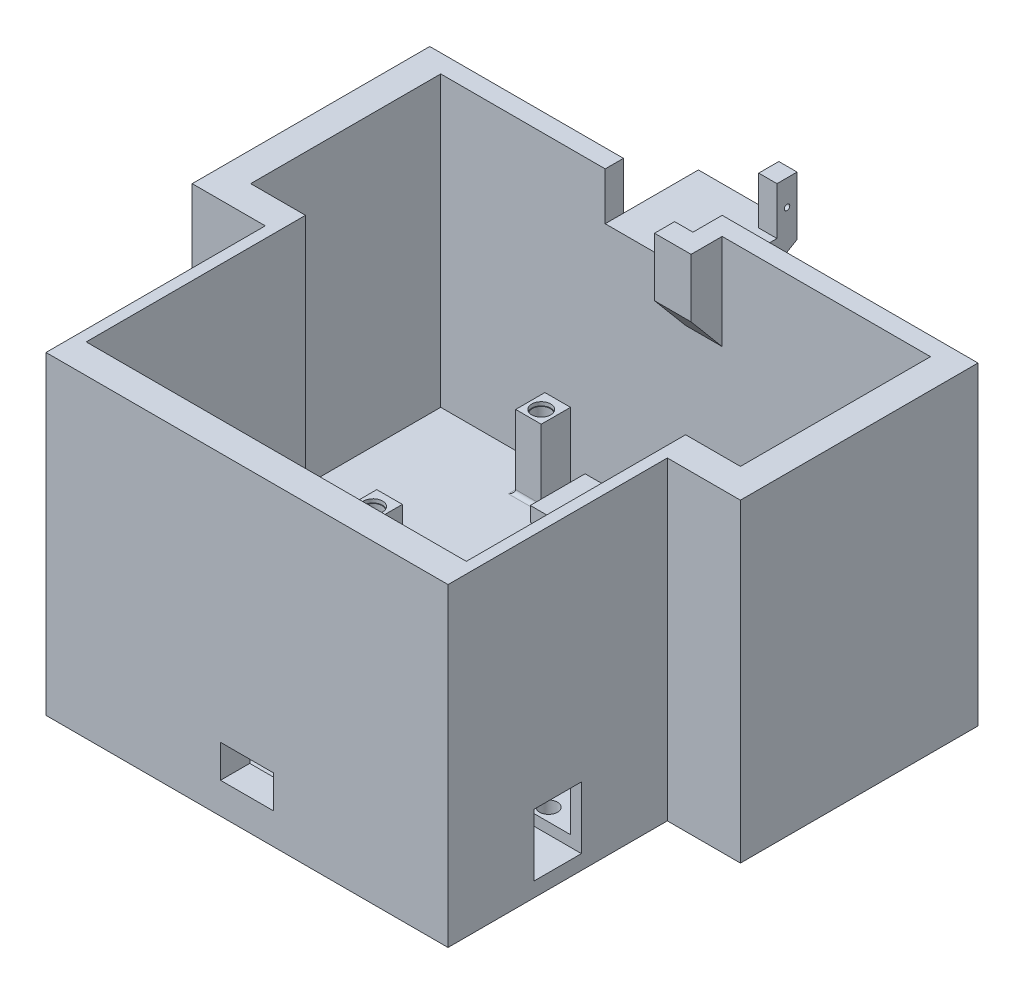
SolidWorks part; units mm, degrees
other "Marca2"
sketch "Croquis35" plane through (-75, 126, -70.5) normal (0, 1, 0) x (1, 0, 0)
other "Marca3"
sketch "Croquis45" plane through (-75, 0, 75) normal (-0.908, -0.0343, 0.4175) x (0.4055, -0.3225, 0.8553)
ref_plane "Alzado" through (0, 0, 0) normal (0, 0, 1) x (1, 0, 0)
ref_plane "Planta" through (0, 0, 0) normal (0, 1, 0) x (1, 0, 0)
ref_plane "Vista lateral" through (0, 0, 0) normal (1, 0, 0) x (0, 0, -1)
sketch "Croquis1" plane through (0, 0, 0) normal (0, 1, 0) x (1, 0, 0)
  line L1 (-75, -75) -> (75, -75)
  line L2 (-75, -75) -> (-75, 75)
  line L3 (-75, 75) -> (75, 75)
  line L4 (75, -75) -> (75, 75)
  line L5 (-75, -75) -> (75, 75) construction
  line L6 (-75, 75) -> (75, -75) construction
  point P0 (0, 0)
  dimension "D1" = 150
  dimension "D2" = 150
extrude "Saliente-Extruir2" add sketch "Croquis1" along normal blind 6
sketch "Croquis3" plane through (0, 6, 0) normal (0, 1, 0) x (1, 0, 0)
  line L0 (-75, 75) -> (-75, -75) construction
  line L1 (-75, -15) -> (-55, -15)
  line L2 (-75, -15) -> (-75, -75)
  line L3 (-75, -75) -> (-55, -75)
  line L4 (-55, -15) -> (-55, -75)
  line L5 (-75, -75) -> (75, -75) construction
  line L6 (0, 0) -> (0, -11.1427) construction
  line L7 (75, -75) -> (55, -75)
  line L8 (55, -15) -> (55, -75)
  line L9 (75, -15) -> (55, -15)
  line L10 (75, -15) -> (75, -75)
  dimension "D1" = 60
  dimension "D2" = 20
extrude "Cortar-Extruir2" cut sketch "Croquis3" against normal through all
sketch "Croquis4" plane through (0, 6, 0) normal (0, 1, 0) x (1, 0, 0)
  line L0 (75, -15) -> (75, 75) construction
  line L1 (-75, 75) -> (75, 75)
  line L2 (-75, 75) -> (-75, 50)
  line L3 (-75, 50) -> (75, 50)
  line L4 (75, 75) -> (75, 50)
  line L6 (-55, -75) -> (55, -75) construction
  dimension "D1" = 125
extrude "Cortar-Extruir3" cut sketch "Croquis4" against normal through all
sketch "Croquis5" plane through (0, 6, 0) normal (0, 1, 0) x (1, 0, 0)
  line L18 (67, -7) -> (67, 42)
  line L19 (67, 42) -> (-67, 42)
  line L20 (-67, 42) -> (-67, -7)
  line L21 (-67, -7) -> (-47, -7)
  line L22 (-47, -7) -> (-47, -67)
  line L23 (-47, -67) -> (47, -67)
  line L24 (47, -67) -> (47, -7)
  line L25 (47, -7) -> (67, -7)
  line L26 (67, -7) -> (67, 42)
  line L27 (67, 42) -> (-67, 42)
  line L28 (-67, 42) -> (-67, -7)
  line L29 (-67, -7) -> (-47, -7)
  line L30 (-47, -7) -> (-47, -67)
  line L31 (-47, -67) -> (47, -67)
  line L32 (47, -67) -> (47, -7)
  line L33 (47, -7) -> (67, -7)
  line L42 (75, -15) -> (75, 50)
  line L43 (75, 50) -> (-75, 50)
  line L44 (-75, 50) -> (-75, -15)
  line L45 (-75, -15) -> (-55, -15)
  line L46 (-55, -15) -> (-55, -75)
  line L47 (-55, -75) -> (55, -75)
  line L48 (55, -75) -> (55, -15)
  line L49 (55, -15) -> (75, -15)
  line L50 (75, -15) -> (75, 50)
  line L51 (75, 50) -> (-75, 50)
  line L52 (-75, 50) -> (-75, -15)
  line L53 (-75, -15) -> (-55, -15)
  line L54 (-55, -15) -> (-55, -75)
  line L55 (-55, -75) -> (55, -75)
  line L56 (55, -75) -> (55, -15)
  line L57 (55, -15) -> (75, -15)
  dimension "D1" = 8
  dimension "D2" = 0
extrude "Saliente-Extruir3" add sketch "Croquis5" along normal blind 80
sketch "Croquis6" plane through (0, 86, 0) normal (0, 1, 0) x (1, 0, 0)
  line L0 (-55, -45) -> (55, -45) construction
  line L1 (-55, -15) -> (-55, -75) construction
  line L2 (55, -75) -> (55, -15) construction
  line L3 (-47, -7) -> (-47, -67) construction
  line L4 (-63, -51.5) -> (-47, -51.5)
  line L5 (-63, -51.5) -> (-63, -38.5)
  line L6 (-63, -38.5) -> (-47, -38.5)
  line L7 (-47, -51.5) -> (-47, -38.5)
  line L8 (-63, -51.5) -> (-47, -38.5) construction
  line L9 (-63, -38.5) -> (-47, -51.5) construction
  line L10 (0, 0) -> (0, -5.6083) construction
  line L11 (63, -38.5) -> (47, -38.5)
  line L12 (47, -51.5) -> (47, -38.5)
  line L13 (63, -51.5) -> (47, -51.5)
  line L14 (63, -51.5) -> (63, -38.5)
  dimension "D1" = 13
extrude "Cortar-Extruir5" cut sketch "Croquis6" against normal up to surface (80 mm away) up to face at (0, 6, 9.75)
sketch "Croquis8" plane through (0, 6, 0) normal (0, 1, 0) x (1, 0, 0)
  line L0 (-55, -45) -> (55, -45) construction
  line L1 (-55, -51.5) -> (-55, -38.5) construction
  line L2 (55, -38.5) -> (55, -51.5) construction
  line L3 (-47, -7) -> (-47, -38.5) construction
  line L4 (-47, -38.5) -> (-26.5, -38.5)
  line L5 (-47, -38.5) -> (-47, -51.5)
  line L6 (-47, -51.5) -> (-26.5, -51.5)
  line L7 (-26.5, -38.5) -> (-26.5, -51.5)
  line L8 (0, 0) -> (0, -18.3886) construction
  line L9 (47, -51.5) -> (26.5, -51.5)
  line L10 (26.5, -38.5) -> (26.5, -51.5)
  line L11 (47, -38.5) -> (26.5, -38.5)
  line L12 (47, -38.5) -> (47, -51.5)
  point P12 (-26.5, -45)
  dimension "D1" = 13
  dimension "D2" = 20.5
sketch "Croquis10" plane through (0, 0, 0) normal (0, -1, 0) x (1, 0, 0)
  line L0 (-75, -50) -> (75, -50) construction
  line L1 (-27.5, -50) -> (27.5, -50)
  line L2 (-27.5, -50) -> (-27.5, -25)
  line L3 (-27.5, -25) -> (27.5, -25)
  line L4 (27.5, -50) -> (27.5, -25)
  point P6 (0, -25)
  dimension "D1" = 55
  dimension "D2" = 25
extrude "Cortar-Extruir6" cut sketch "Croquis10" against normal blind 5
extrude "Cortar-Extruir7" cut sketch "Croquis8" against normal blind 2
sketch "Croquis12" plane through (0, 6, 0) normal (0, 1, 0) x (1, 0, 0)
  line L0 (-47, -38.5) -> (-47, -51.5) construction
  line L1 (-55, -38.5) -> (-47, -38.5)
  line L2 (-55, -38.5) -> (-55, -51.5)
  line L3 (-55, -51.5) -> (-47, -51.5)
  line L4 (-47, -38.5) -> (-47, -51.5)
  line L5 (-47, -51.5) -> (-47, -38.5) construction
  line L6 (0, 0) -> (0, -14.0834) construction
  line L7 (55, -51.5) -> (47, -51.5)
  line L8 (47, -38.5) -> (47, -51.5)
  line L9 (55, -38.5) -> (47, -38.5)
  line L10 (55, -38.5) -> (55, -51.5)
extrude "Cortar-Extruir8" cut sketch "Croquis12" against normal up to surface (2 mm away) up to face at (-36.75, 4, 45)
sketch "Croquis15" plane through (0, 6, 0) normal (0, 1, 0) x (1, 0, 0)
  line L16 (-47, -7) -> (-47, -38.5)
  line L17 (-47, -38.5) -> (-26.5, -38.5)
  line L18 (-26.5, -38.5) -> (-26.5, -51.5)
  line L19 (-26.5, -51.5) -> (-47, -51.5)
  line L20 (-47, -51.5) -> (-47, -67)
  line L21 (-47, -67) -> (47, -67)
  line L22 (47, -67) -> (47, -51.5)
  line L23 (47, -51.5) -> (26.5, -51.5)
  line L24 (26.5, -51.5) -> (26.5, -38.5)
  line L25 (26.5, -38.5) -> (47, -38.5)
  line L26 (47, -38.5) -> (47, -7)
  line L27 (47, -7) -> (67, -7)
  line L28 (67, -7) -> (67, 42)
  line L29 (67, 42) -> (-67, 42)
  line L30 (-67, 42) -> (-67, -7)
  line L31 (-67, -7) -> (-47, -7)
  line L32 (-47, -7) -> (-47, -38.5)
  line L33 (-47, -38.5) -> (-26.5, -38.5)
  line L34 (-26.5, -38.5) -> (-26.5, -51.5)
  line L35 (-26.5, -51.5) -> (-47, -51.5)
  line L36 (-47, -51.5) -> (-47, -67)
  line L37 (-47, -67) -> (47, -67)
  line L38 (47, -67) -> (47, -51.5)
  line L39 (47, -51.5) -> (26.5, -51.5)
  line L40 (26.5, -51.5) -> (26.5, -38.5)
  line L41 (26.5, -38.5) -> (47, -38.5)
  line L42 (47, -38.5) -> (47, -7)
  line L43 (47, -7) -> (67, -7)
  line L44 (67, -7) -> (67, 42)
  line L45 (67, 42) -> (-67, 42)
  line L46 (-67, 42) -> (-67, -7)
  line L47 (-67, -7) -> (-47, -7)
  dimension "D1" = 0
extrude "Saliente-Extruir6" add sketch "Croquis15" along normal blind 1
sketch "Croquis16" plane through (-55, 0, 0) normal (-1, 0, 0) x (0, 0, 1)
  line L0 (51.5, 16) -> (38.5, 16) construction
  line L1 (51.5, 86) -> (51.5, 4) construction
  line L2 (38.5, 4) -> (38.5, 86) construction
  line L3 (51.5, 4) -> (38.5, 4) construction
  dimension "D1" = 12
sketch "Croquis17" plane through (0, 86, 0) normal (0, 1, 0) x (1, 0, 0)
  line L0 (0, 0) -> (0, -9.7124) construction
  line L1 (-55, -38.5) -> (-47, -38.5)
  line L2 (-55, -38.5) -> (-55, -51.5)
  line L3 (-55, -51.5) -> (-47, -51.5)
  line L4 (-47, -38.5) -> (-47, -51.5)
  line L5 (55, -51.5) -> (47, -51.5)
  line L6 (47, -38.5) -> (47, -51.5)
  line L7 (55, -38.5) -> (47, -38.5)
  line L8 (55, -38.5) -> (55, -51.5)
extrude "Saliente-Extruir7" add sketch "Croquis17" against normal blind 65
sketch "Croquis20" plane through (0, 0, -50) normal (0, 0, -1) x (-1, 0, 0)
  line L0 (0, 0) -> (0, 36.986) construction
  line L2 (0, 73) -> (22, 73)
  line L3 (0, 73) -> (0, 86)
  line L4 (0, 86) -> (22, 86)
  line L5 (22, 73) -> (22, 86)
  line L6 (0, 73) -> (22, 86) construction
  line L7 (0, 86) -> (22, 73) construction
  line L8 (-75, 86) -> (75, 86) construction
  point P3 (11, 79.5)
  dimension "D1" = 13
  dimension "D2" = 22
extrude "Cortar-Extruir9" cut sketch "Croquis20" against normal up to next
sketch "Croquis23" plane through (0, 86, 0) normal (0, 1, 0) x (1, 0, 0)
  line L0 (-75, 50) -> (-75, -15) construction
  line L1 (-74, 11) -> (-68, 11)
  line L2 (-74, 11) -> (-74, 24)
  line L3 (-74, 24) -> (-68, 24)
  line L4 (-68, 11) -> (-68, 24)
  line L5 (-74, 11) -> (-68, 24) construction
  line L6 (-74, 24) -> (-68, 11) construction
  line L7 (-75, 50) -> (-75, -15) construction
  line L8 (0, 0) -> (0, 8.906) construction
  line L9 (74, 24) -> (68, 24)
  line L10 (68, 11) -> (68, 24)
  line L11 (74, 11) -> (68, 11)
  line L12 (74, 11) -> (74, 24)
  line L22 (-55, -75) -> (55, -75) construction
  line L23 (47, -67) -> (47, -75) construction
  line L24 (-6.5, -74) -> (6.5, -74)
  line L25 (-6.5, -74) -> (-6.5, -68)
  line L26 (-6.5, -68) -> (6.5, -68)
  line L27 (6.5, -74) -> (6.5, -68)
  line L28 (-6.5, -74) -> (6.5, -68) construction
  line L29 (-6.5, -68) -> (6.5, -74) construction
  line L30 (-47, -67) -> (47, -67) construction
  point P0 (-71, 17.5)
  point P12 (-75, 17.5)
  point P20 (0, -71)
  point P38 (0, -75)
  dimension "D1" = 4
  dimension "D2" = 6
  dimension "D3" = 13
  dimension "D4" = 13
  dimension "D5" = 6
  dimension "D6" = 1
extrude "Cortar-Extruir10" cut sketch "Croquis23" against normal blind 3
sketch "Croquis24" plane through (0, 73, 0) normal (0, 1, 0) x (1, 0, 0)
  line L0 (75, 50) -> (0, 50) construction
  line L1 (-22, 70.5) -> (0, 70.5)
  line L2 (-22, 70.5) -> (-22, 36.5)
  line L3 (-22, 36.5) -> (0, 36.5)
  line L4 (0, 70.5) -> (0, 36.5)
  dimension "D1" = 22
  dimension "D2" = 34
  dimension "D3" = 13.5
extrude "Saliente-Extruir9" add sketch "Croquis24" against normal blind 3
sketch "Croquis25" plane through (-22, 0, 0) normal (-1, 0, 0) x (0, 0, 1)
  line L0 (-70.5, 73) -> (-36.5, 73) construction
  line L1 (-42, 73) -> (-42, 102.2698) construction
  line L6 (-42, 70) -> (-36.5, 70) construction
  line L21 (-36.5, 73) -> (-36.5, 70)
  line L25 (-50, 73) -> (-70.5, 73)
  line L26 (-70.5, 73) -> (-70.5, 70)
  line L28 (-70.5, 70) -> (-50, 58.1643)
  line L29 (-50, 0) -> (-50, 86) construction
  line L30 (-50, 58.1643) -> (-50, 73)
  line L34 (-36.5, 70) -> (-46.454, 58.1643)
  line L35 (-46.454, 58.1643) -> (-46.454, 73)
  line L36 (-46.454, 73) -> (-36.5, 73)
  dimension "D1" = 60
  dimension "D2" = 9.954
extrude "Saliente-Extruir10" add sketch "Croquis25" against normal blind 27
sketch "Croquis27" plane through (0, 73, 0) normal (0, 1, 0) x (1, 0, 0)
  line L10 (-22, 42) -> (-22, 65) construction
  line L11 (-22, 42) -> (-22, 36.5) construction
  line L12 (-22, 70.5) -> (-22, 50) construction
  line L13 (-22, 65) -> (0, 65) construction
  line L14 (0, 65) -> (0, 42) construction
  line L15 (0, 42) -> (-22, 42) construction
  line L27 (75, 50) -> (0, 50) construction
  line L33 (5, 70.5) -> (0, 70.5)
  line L34 (5, 70.5) -> (5, 65)
  line L35 (5, 65) -> (0, 65)
  line L36 (0, 70.5) -> (0, 65)
  line L37 (5, 36.5) -> (0, 36.5)
  line L38 (5, 36.5) -> (5, 42)
  line L39 (5, 42) -> (0, 42)
  line L40 (0, 36.5) -> (0, 42)
  dimension "D1" = 15
  dimension "D2" = 22
  dimension "D3" = 23
extrude "Saliente-Extruir14" add sketch "Croquis27" along normal up to vertex (13 mm away)
sketch "Croquis30" plane through (0, 86, 0) normal (0, 1, 0) x (1, 0, 0)
  line L0 (-22, 42) -> (-22, 50) construction
  line L1 (-67, 42) -> (-22, 42)
  line L2 (-67, 42) -> (-67, 45)
  line L3 (-67, 45) -> (-22, 45)
  line L4 (-22, 42) -> (-22, 45)
  line L5 (75, 50) -> (0, 50) construction
  line L6 (5, 42) -> (67, 42)
  line L7 (5, 42) -> (5, 45)
  line L8 (5, 45) -> (67, 45)
  line L9 (67, 42) -> (67, 45)
  line L10 (-22, 50) -> (-75, 50) construction
  line L11 (-55, -15) -> (-55, -75) construction
  line L12 (-47, -7) -> (-52, -7)
  line L13 (-47, -7) -> (-47, -67)
  line L14 (-47, -67) -> (-52, -67)
  line L15 (-52, -7) -> (-52, -67)
  line L16 (0, 0) -> (0, -10.7423) construction
  line L17 (47, -67) -> (52, -67)
  line L18 (52, -7) -> (52, -67)
  line L19 (47, -7) -> (52, -7)
  line L20 (47, -7) -> (47, -67)
  dimension "D1" = 5
  dimension "D2" = 5
  dimension "D3" = 3
extrude "Cortar-Extruir11" cut sketch "Croquis30" against normal up to surface (79 mm away) up to face at (0, 7, 27.375)
sketch "Croquis31" plane through (5, 0, 0) normal (1, 0, 0) x (0, 0, -1)
  line L0 (36.5, 70) -> (37.3986, 68.9316) construction
  line L1 (45, 86) -> (45, 7) construction
  line L2 (42, 63.4603) -> (42, 93.123) construction
  line L3 (42, 7) -> (42, 63.4603) construction
  line L4 (42, 63.4603) -> (42, 7)
  line L5 (42, 7) -> (45, 7)
  line L6 (45, 7) -> (45, 59.8932)
  line L7 (45, 59.8932) -> (42, 63.4603)
  line L8 (42, 63.4603) -> (36.5, 70) construction
  dimension "D1" = 139.936
extrude "Cortar-Extruir12" cut sketch "Croquis31" against normal up to vertex (27 mm away) up to point (-22, 73, -45)
sketch "Croquis34" plane through (0, 7, 0) normal (0, 1, 0) x (1, 0, 0)
  line L0 (75, -15) -> (75, 50) construction
  line L1 (-27.5, 30) -> (27.5, 30)
  line L2 (-27.5, 30) -> (-27.5, 45)
  line L3 (-27.5, 45) -> (27.5, 45)
  line L4 (27.5, 30) -> (27.5, 45)
  line L5 (-27.5, 30) -> (27.5, 45) construction
  line L6 (-27.5, 45) -> (27.5, 30) construction
  line L7 (-75, 50) -> (-75, -15) construction
  line L8 (67, 45) -> (-67, 45) construction
  point P0 (0, 37.5)
  dimension "D1" = 47.5
  dimension "D2" = 47.5
  dimension "D3" = 15
extrude "Saliente-Extruir16" add sketch "Croquis34" along normal blind 4
sketch "Croquis38" plane through (0, 7, 0) normal (0, 1, 0) x (1, 0, 0)
  line L0 (-32.75, 38.75) -> (32.75, 38.75) construction
  line L1 (32.75, 38.75) -> (32.75, -7.25) construction
  line L2 (32.75, -7.25) -> (-32.75, -7.25) construction
  line L3 (-32.75, -7.25) -> (-32.75, 38.75) construction
  line L4 (-19, -22.25) -> (19, -22.25) construction
  line L5 (19, -22.25) -> (19, -60.25) construction
  line L6 (19, -60.25) -> (-19, -60.25) construction
  line L7 (-19, -60.25) -> (-19, -22.25) construction
  line L8 (-52, -67) -> (52, -67) construction
  line L9 (67, 45) -> (27.5, 45) construction
  line L10 (0, -7.25) -> (0, 6.4937) construction
  line L11 (-29.25, 34.75) -> (-36.25, 34.75)
  line L12 (-29.25, 34.75) -> (-29.25, 42.75)
  line L13 (-29.25, 42.75) -> (-36.25, 42.75)
  line L14 (-36.25, 34.75) -> (-36.25, 42.75)
  line L15 (-29.25, 34.75) -> (-36.25, 42.75) construction
  line L16 (-29.25, 42.75) -> (-36.25, 34.75) construction
  line L17 (29.25, 42.75) -> (36.25, 42.75)
  line L18 (36.25, 34.75) -> (36.25, 42.75)
  line L19 (29.25, 34.75) -> (36.25, 34.75)
  line L20 (29.25, 34.75) -> (29.25, 42.75)
  line L21 (-32.75, 15.75) -> (-24.9135, 15.75) construction
  line L22 (29.25, -3.25) -> (29.25, -11.25)
  line L23 (29.25, -3.25) -> (36.25, -3.25)
  line L24 (36.25, -3.25) -> (36.25, -11.25)
  line L25 (29.25, -11.25) -> (36.25, -11.25)
  line L26 (-29.25, -11.25) -> (-36.25, -11.25)
  line L27 (-36.25, -3.25) -> (-36.25, -11.25)
  line L28 (-29.25, -3.25) -> (-36.25, -3.25)
  line L29 (-29.25, -3.25) -> (-29.25, -11.25)
  line L30 (15.5, -18.25) -> (22.5, -18.25)
  line L31 (-15.5, -26.25) -> (-22.5, -26.25)
  line L32 (-15.5, -26.25) -> (-15.5, -18.25)
  line L33 (-15.5, -18.25) -> (-22.5, -18.25)
  line L34 (-22.5, -26.25) -> (-22.5, -18.25)
  line L35 (-15.5, -26.25) -> (-22.5, -18.25) construction
  line L36 (-15.5, -18.25) -> (-22.5, -26.25) construction
  line L37 (22.5, -26.25) -> (22.5, -18.25)
  line L38 (15.5, -26.25) -> (22.5, -26.25)
  line L39 (15.5, -26.25) -> (15.5, -18.25)
  line L40 (15.5, -18.25) -> (22.5, -26.25) construction
  line L41 (15.5, -26.25) -> (22.5, -18.25) construction
  line L42 (-19, -41.25) -> (-6.0761, -41.25) construction
  line L43 (15.5, -56.25) -> (15.5, -64.25)
  line L44 (15.5, -56.25) -> (22.5, -56.25)
  line L45 (22.5, -56.25) -> (22.5, -64.25)
  line L46 (15.5, -64.25) -> (22.5, -64.25)
  line L47 (-15.5, -64.25) -> (-22.5, -64.25)
  line L48 (-22.5, -56.25) -> (-22.5, -64.25)
  line L49 (-15.5, -56.25) -> (-22.5, -56.25)
  line L50 (-15.5, -56.25) -> (-15.5, -64.25)
  point P2 (0, 38.75)
  point P32 (0, -22.25)
  dimension "D1" = 46
  dimension "D2" = 65.5
  dimension "D3" = 38
  dimension "D4" = 38
  dimension "D5" = 6.25
  dimension "D6" = 6.75
  dimension "D7" = 8
  dimension "D8" = 7
  dimension "D9" = 8
  dimension "D10" = 7
extrude "Saliente-Extruir18" add sketch "Croquis38" along normal blind 20
sketch "Croquis39" plane through (0, 27, 0) normal (0, 1, 0) x (1, 0, 0)
  line L0 (-32.75, 38.25) -> (32.75, 38.25) construction
  line L1 (32.75, 38.25) -> (32.75, -7.75) construction
  line L2 (32.75, -7.75) -> (-32.75, -7.75) construction
  line L3 (-32.75, -7.75) -> (-32.75, 38.25) construction
  line L4 (-19, -22.25) -> (19, -22.25) construction
  line L5 (19, -22.25) -> (19, -60.25) construction
  line L6 (19, -60.25) -> (-19, -60.25) construction
  line L7 (-19, -60.25) -> (-19, -22.25) construction
  line L8 (0, -7.75) -> (0, 56.9333) construction
  line L13 (67, 45) -> (27.5, 45) construction
  line L19 (-32.75, 15.25) -> (-56.3736, 15.25) construction
  line L40 (-19, -41.25) -> (-37.5362, -41.25) construction
  line L49 (-52, -67) -> (52, -67) construction
  circle A0 centre (-32.75, 38.25) radius 2.6
  circle A1 centre (32.75, 38.25) radius 2.6
  circle A2 centre (32.75, -7.75) radius 2.6
  circle A3 centre (-32.75, -7.75) radius 2.6
  circle A4 centre (-19, -22.25) radius 2.6
  circle A5 centre (19, -22.25) radius 2.6
  circle A6 centre (19, -60.25) radius 2.6
  circle A7 centre (-19, -60.25) radius 2.6
  point P15 (0, -22.25)
  dimension "D7" = 5.2
  dimension "D8" = 5.2
  dimension "D1" = 38
  dimension "D2" = 38
  dimension "D3" = 46
  dimension "D4" = 65.5
  dimension "D5" = 6.75
  dimension "D6" = 6.75
extrude "Cortar-Extruir13" cut sketch "Croquis39" against normal blind 1
sketch "Croquis40" plane through (0, 26, 0) normal (0, 1, 0) x (1, 0, 0)
  line L0 (-32.75, 38.25) -> (32.75, 38.25) construction
  line L1 (32.75, 38.25) -> (32.75, -7.75) construction
  line L2 (32.75, -7.75) -> (-32.75, -7.75) construction
  line L3 (-32.75, -7.75) -> (-32.75, 38.25) construction
  line L4 (-19, -22.25) -> (19, -22.25) construction
  line L5 (19, -22.25) -> (19, -60.25) construction
  line L6 (19, -60.25) -> (-19, -60.25) construction
  line L7 (-19, -60.25) -> (-19, -22.25) construction
  line L8 (0, -7.75) -> (0, 98.1871) construction
  line L9 (-32.75, 15.25) -> (-78.504, 15.25) construction
  line L10 (-19, -41.25) -> (-59.6666, -41.25) construction
  line L11 (-52, -67) -> (52, -67) construction
  line L12 (67, 45) -> (5, 45) construction
  circle A0 centre (-32.75, 38.25) radius 2.425
  circle A1 centre (32.75, 38.25) radius 2.425
  circle A2 centre (32.75, -7.75) radius 2.425
  circle A3 centre (-32.75, -7.75) radius 2.425
  circle A4 centre (-19, -22.25) radius 2.425
  circle A5 centre (19, -22.25) radius 2.425
  circle A6 centre (19, -60.25) radius 2.425
  circle A7 centre (-19, -60.25) radius 2.425
  dimension "D7" = 4.85
  dimension "D8" = 4.85
  dimension "D1" = 46
  dimension "D2" = 65.5
  dimension "D3" = 38
  dimension "D4" = 38
  dimension "D5" = 6.75
  dimension "D6" = 6.75
extrude "Cortar-Extruir14" cut sketch "Croquis40" against normal blind 22
sketch "Croquis42" plane through (5, 0, 0) normal (1, 0, 0) x (0, 0, -1)
  line L0 (50, 73) -> (65, 73) construction
  line L1 (65, 86) -> (70.5, 86) construction
  line L2 (40.25, 79) -> (40.25, 86) construction
  line L3 (-15, 86) -> (50, 86) construction
  line L4 (42, 73) -> (65, 73) construction
  circle A0 centre (67.75, 79) radius 0.75
  circle A1 centre (40.25, 79) radius 0.75
  point P9 (67.75, 86)
  dimension "D2" = 1.5
  dimension "D3" = 1.5
  dimension "D5" = 6
  dimension "D1" = 6
  dimension "D4" = 27.5
extrude "Cortar-Extruir15" cut sketch "Croquis42" against normal mid plane 15
sketch "Croquis44" plane through (0, 0, 75) normal (0, 0, 1) x (1, 0, 0)
  line L1 (-7.25, 17.5) -> (7.25, 17.5)
  line L2 (-7.25, 17.5) -> (-7.25, 8.5)
  line L3 (-7.25, 8.5) -> (7.25, 8.5)
  line L4 (7.25, 17.5) -> (7.25, 8.5)
  line L5 (-7.25, 17.5) -> (7.25, 8.5) construction
  line L6 (-7.25, 8.5) -> (7.25, 17.5) construction
  point P0 (0, 13)
  dimension "D1" = 14.5
  dimension "D2" = 9
  dimension "D3" = 13
extrude "Cortar-Extruir17" cut sketch "Croquis44" against normal up to surface (8 mm away) up to face at (0, 46.5, 67)
fillet "Redondeo2" radius 1 4 edges at (-32.75, 7, -42.75) (-29.25, 7, -38.75) (-36.25, 7, -38.75) (-32.75, 7, -34.75)
fillet "Redondeo3" radius 1 28 edges at (-19, 7, 64.25) (-22.5, 7, 60.25) (-15.5, 7, 60.25) (-19, 7, 56.25) (-19, 7, 26.25) (-22.5, 7, 22.25) (-15.5, 7, 22.25) (-19, 7, 18.25) (-32.75, 7, 3.25) (-36.25, 7, 7.25) (-29.25, 7, 7.25) (-32.75, 7, 11.25) (19, 7, 64.25) (22.5, 7, 60.25) (15.5, 7, 60.25) (19, 7, 56.25) (29.25, 7, 7.25) (32.75, 7, 11.25) (32.75, 7, 3.25) (36.25, 7, 7.25) (19, 7, 18.25) (22.5, 7, 22.25) (15.5, 7, 22.25) (19, 7, 26.25) (32.75, 7, -42.75) (29.25, 7, -38.75) (36.25, 7, -38.75) (32.75, 7, -34.75)
sketch "Croquis48" plane through (0, 11, 0) normal (0, 1, 0) x (1, 0, 0)
  line L0 (27.5, 25) -> (27.5, 50) construction
  circle A0 centre (20, 37.5) radius 2.6
  point P5 (27.5, 37.5)
  dimension "D2" = 5.2
  dimension "D3" = 7.5
  dimension "D1" = 25
extrude "Cortar-Extruir19" cut sketch "Croquis48" against normal blind 1
mirror "Simetría6" about plane through (0, 0, 0) normal (1, 0, 0) of "Cortar-Extruir19"
sketch "Croquis49" plane through (0, 10, 0) normal (0, 1, 0) x (1, 0, 0)
  line L0 (27.5, 25) -> (27.5, 50) construction
  circle A0 centre (20, 37.5) radius 2.425
  dimension "D2" = 4.85
  dimension "D1" = 25
extrude "Cortar-Extruir20" cut sketch "Croquis49" against normal through all
mirror "Simetría7" about plane through (0, 0, 0) normal (1, 0, 0) of "Cortar-Extruir20"
sketch "Croquis50" plane through (0, 7, 0) normal (0, 1, 0) x (1, 0, 0)
  line L1 (-52, -7) -> (-52, -67) construction
  line L3 (-26.5, -45) -> (-41.1105, -45) construction
  line L4 (-26.5, -38.5) -> (-26.5, -51.5) construction
  line L6 (0, -47.3) -> (0, 47.3) construction
  circle A0 centre (-42.5, -35) radius 2.425
  circle A1 centre (-42.5, -55) radius 2.425
  circle A2 centre (42.5, -55) radius 2.425
  circle A3 centre (42.5, -35) radius 2.425
  dimension "D2" = 10
  dimension "D3" = 4.85
  dimension "D1" = 9.5
extrude "Cortar-Extruir21" cut sketch "Croquis50" against normal through all
sketch "Croquis51" plane through (0, 0, 0) normal (0, -1, 0) x (1, 0, 0)
  line L0 (-55, 45) -> (-46.5147, 45) construction
  line L1 (-55, 51.5) -> (-55, 38.5) construction
  line L2 (0, -47.3) -> (0, 47.3) construction
  circle A0 centre (-42.5, 55) radius 2.6
  circle A1 centre (-42.5, 35) radius 2.6
  circle A2 centre (42.5, 35) radius 2.6
  circle A3 centre (42.5, 55) radius 2.6
  dimension "D1" = 5.2
extrude "Cortar-Extruir22" cut sketch "Croquis51" against normal blind 1
sketch "Croquis56" plane through (0, 86, 0) normal (0, 1, 0) x (1, 0, 0)
  line L0 (0, 65) -> (0, 42) construction
  line L2 (0, 42) -> (5, 42)
  line L3 (0, 42) -> (0, 50)
  line L4 (0, 50) -> (5, 50)
  line L5 (5, 42) -> (5, 50)
  line L10 (75, 50) -> (0, 50) construction
  dimension "D1" = 8
  dimension "D3" = 5
extrude "Cortar-Extruir24" cut sketch "Croquis56" against normal up to surface (13 mm away) up to face at (-7.8, 73, -53.9)
sketch "Croquis59" plane through (5, 0, 0) normal (1, 0, 0) x (0, 0, -1)
  line L6 (45, 73) -> (42, 73)
  line L7 (42, 73) -> (42, 86)
  line L8 (42, 86) -> (36.5, 86)
  line L9 (36.5, 86) -> (36.5, 70)
  line L10 (36.5, 70) -> (45, 59.8932)
  line L11 (45, 59.8932) -> (45, 73)
  line L12 (45, 73) -> (42, 73)
  line L13 (42, 73) -> (42, 86)
  line L14 (42, 86) -> (36.5, 86)
  line L15 (36.5, 86) -> (36.5, 70)
  line L16 (36.5, 70) -> (45, 59.8932)
  line L17 (45, 59.8932) -> (45, 73)
  dimension "D1" = 0
extrude "Saliente-Extruir20" add sketch "Croquis59" along normal blind 5
sketch "Croquis60" plane through (0, 86, 0) normal (0, 1, 0) x (1, 0, 0)
  line L1 (5, 45) -> (10, 45)
  line L2 (5, 45) -> (5, 42)
  line L3 (5, 42) -> (10, 42)
  line L4 (10, 45) -> (10, 42)
extrude "Saliente-Extruir21" add sketch "Croquis60" against normal up to surface (13 mm away) up to face at (-4.0769, 73, -51)
sketch "Croquis61" plane through (0, 73, 0) normal (0, 1, 0) x (1, 0, 0)
  line L1 (-22, 36.5) -> (0, 36.5)
  line L2 (-22, 36.5) -> (-22, 45)
  line L3 (-22, 45) -> (0, 45)
  line L4 (0, 36.5) -> (0, 45)
extrude "Cortar-Extruir25" cut sketch "Croquis61" against normal blind 15
sketch "Croquis62" plane through (0, 86, 0) normal (0, 1, 0) x (1, 0, 0)
  line L24 (5, 50) -> (5, 42)
  line L25 (5, 42) -> (0, 42)
  line L26 (0, 42) -> (0, 36.5)
  line L27 (0, 36.5) -> (10, 36.5)
  line L28 (10, 36.5) -> (10, 45)
  line L29 (10, 45) -> (67, 45)
  line L30 (67, 45) -> (67, -7)
  line L31 (67, -7) -> (52, -7)
  line L32 (52, -7) -> (52, -67)
  line L33 (52, -67) -> (-52, -67)
  line L34 (-52, -67) -> (-52, -7)
  line L35 (-52, -7) -> (-67, -7)
  line L36 (-67, -7) -> (-67, 45)
  line L37 (-67, 45) -> (-22, 45)
  line L38 (-22, 45) -> (-22, 50)
  line L39 (-22, 50) -> (-75, 50)
  line L40 (-75, 50) -> (-75, -15)
  line L41 (-75, -15) -> (-55, -15)
  line L42 (-55, -15) -> (-55, -75)
  line L43 (-55, -75) -> (55, -75)
  line L44 (55, -75) -> (55, -15)
  line L45 (55, -15) -> (75, -15)
  line L46 (75, -15) -> (75, 50)
  line L47 (75, 50) -> (5, 50)
  line L48 (5, 50) -> (5, 42)
  line L49 (5, 42) -> (0, 42)
  line L50 (0, 42) -> (0, 36.5)
  line L51 (0, 36.5) -> (10, 36.5)
  line L52 (10, 36.5) -> (10, 45)
  line L53 (10, 45) -> (67, 45)
  line L54 (67, 45) -> (67, -7)
  line L55 (67, -7) -> (52, -7)
  line L56 (52, -7) -> (52, -67)
  line L57 (52, -67) -> (-52, -67)
  line L58 (-52, -67) -> (-52, -7)
  line L59 (-52, -7) -> (-67, -7)
  line L60 (-67, -7) -> (-67, 45)
  line L61 (-67, 45) -> (-22, 45)
  line L62 (-22, 45) -> (-22, 50)
  line L63 (-22, 50) -> (-75, 50)
  line L64 (-75, 50) -> (-75, -15)
  line L65 (-75, -15) -> (-55, -15)
  line L66 (-55, -15) -> (-55, -75)
  line L67 (-55, -75) -> (55, -75)
  line L68 (55, -75) -> (55, -15)
  line L69 (55, -15) -> (75, -15)
  line L70 (75, -15) -> (75, 50)
  line L71 (75, 50) -> (5, 50)
  dimension "D1" = 0
extrude "Saliente-Extruir22" add sketch "Croquis62" against normal blind 1
